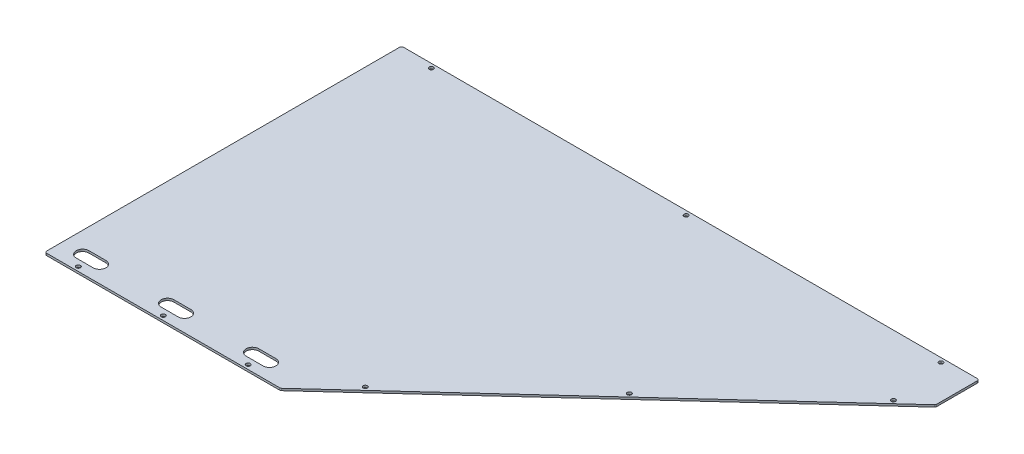
SolidWorks part; units mm, degrees
material "PE High Density"
ref_plane "Front Plane" through (0, 0, 0) normal (0, 0, 1) x (1, 0, 0)
ref_plane "Top Plane" through (0, 0, 0) normal (0, 1, 0) x (1, 0, 0)
ref_plane "Right Plane" through (0, 0, 0) normal (1, 0, 0) x (0, 0, -1)
sketch "Sketch1" plane through (0, 0, 0) normal (0, 1, 0) x (1, 0, 0)
  line L0 (0, 0) -> (352.425, 0)
  line L1 (352.425, 0) -> (863.6, 468.4056)
  line L2 (863.6, 533.4) -> (0, 533.4)
  line L7 (0, 533.4) -> (0, 0)
  line L8 (863.6, 533.4) -> (863.6, 468.4056)
  dimension "D4" = 863.6
  dimension "D1" = 352.425
  dimension "D2" = 533.4
  dimension "D3" = 137.5
extrude "Boss-Extrude1" add sketch "Sketch1" along normal blind 3.175
fillet "Fillet1" radius 3.175 5 edges at (0, 1.5875, 0) (863.6, 1.5875, -533.4) (863.6, 1.5875, -468.4056) (352.425, 1.5875, 0) (0, 1.5875, -533.4)
sketch "Sketch2" plane through (0, 3.175, 0) normal (0, 1, 0) x (1, 0, 0)
  line L0 (43.8327, 6.35) -> (297.8327, 6.35) construction
  line L1 (414.0534, 65.0848) -> (826.0439, 442.6046) construction
  line L2 (353.3353, 0.8341) -> (862.57, 467.4618) construction
  line L3 (3.175, 0) -> (351.1903, 0) construction
  line L4 (603.6627, 238.8297) -> (607.9527, 234.148) construction
  line L5 (50.8, 527.05) -> (812.8, 527.05) construction
  line L6 (860.425, 533.4) -> (3.175, 533.4) construction
  point P0 (43.8327, 6.35)
  point P1 (170.8327, 6.35)
  point P2 (297.8327, 6.35)
  point P3 (414.0534, 65.0848)
  point P4 (620.0486, 253.8447)
  point P5 (826.0439, 442.6046)
  point P10 (607.9527, 234.148)
  point P16 (177.1827, 0)
  point P20 (431.8, 533.4)
  point P21 (431.8, 527.05)
  dimension "D1" = 6.35
  dimension "D2" = 6.35
  dimension "D3" = 254
  dimension "D4" = 558.8
  dimension "D5" = 6.35
  dimension "D6" = 22.225
  dimension "D7" = 6.35
  dimension "D8" = 762
hole_wizard "1/4 (0.25) Diameter Hole1" positions "Sketch3" profile "Sketch4" hole size "1/4" standard "ANSI Inch" end condition through all
sketch "Sketch3" plane through (0, 3.175, 0) normal (0, 1, 0) x (1, 0, 0)
  point P0 (43.8327, 6.35)
  point P3 (170.8327, 6.35)
  point P6 (297.8327, 6.35)
  point P9 (414.0534, 65.0848)
  point P12 (620.0486, 253.8447)
  point P15 (826.0439, 442.6046)
  point P19 (50.8, 527.05)
  point P22 (431.8, 527.05)
  point P25 (812.8, 527.05)
sketch "Sketch4" plane through (43.8327, 3.175, -6.35) normal (1, 0, 0) x (0, 0, 1)
  line L0 (0, 0) -> (0, 3.175)
  line L1 (0, 3.175) -> (3.175, 3.175)
  line L2 (3.175, 3.175) -> (3.175, 0)
  line L5 (3.175, 0) -> (0, 0)
  line L11 (0, -6.35) -> (0, 107.95) construction
  dimension "Thru Hole Dia." = 6.35
  dimension "Thru Hole Depth" = 3.175
sketch "Sketch5" plane through (0, 3.175, 0) normal (0, 1, 0) x (1, 0, 0)
  line L0 (31.1327, 25.4) -> (56.5327, 25.4) construction
  line L1 (31.1327, 34.925) -> (56.5327, 34.925)
  line L2 (31.1327, 15.875) -> (56.5327, 15.875)
  line L3 (158.1327, 25.4) -> (183.5327, 25.4) construction
  line L4 (158.1327, 34.925) -> (183.5327, 34.925)
  line L5 (158.1327, 15.875) -> (183.5327, 15.875)
  line L6 (285.1327, 25.4) -> (310.5327, 25.4) construction
  line L7 (285.1327, 34.925) -> (310.5327, 34.925)
  line L8 (285.1327, 15.875) -> (310.5327, 15.875)
  circle A0 centre (297.8327, 6.35) radius 3.175 construction
  circle A1 centre (170.8327, 6.35) radius 3.175 construction
  circle A2 centre (43.8327, 6.35) radius 3.175 construction
  circle A3 centre (297.8327, 6.35) radius 3.175
  circle A4 centre (170.8327, 6.35) radius 3.175
  circle A5 centre (43.8327, 6.35) radius 3.175
  arc A6 (31.1327, 34.925) -> (31.1327, 15.875) centre (31.1327, 25.4) ccw
  arc A7 (56.5327, 15.875) -> (56.5327, 34.925) centre (56.5327, 25.4) ccw
  arc A8 (158.1327, 34.925) -> (158.1327, 15.875) centre (158.1327, 25.4) ccw
  arc A9 (183.5327, 15.875) -> (183.5327, 34.925) centre (183.5327, 25.4) ccw
  arc A10 (285.1327, 34.925) -> (285.1327, 15.875) centre (285.1327, 25.4) ccw
  arc A11 (310.5327, 15.875) -> (310.5327, 34.925) centre (310.5327, 25.4) ccw
  point P11 (43.8327, 25.4)
  point P17 (170.8327, 25.4)
  point P24 (297.8327, 25.4)
  dimension "D1" = 9.525
  dimension "D2" = 19.05
  dimension "D3" = 25.4
extrude "Cut-Extrude1" cut sketch "Sketch5" against normal through all
